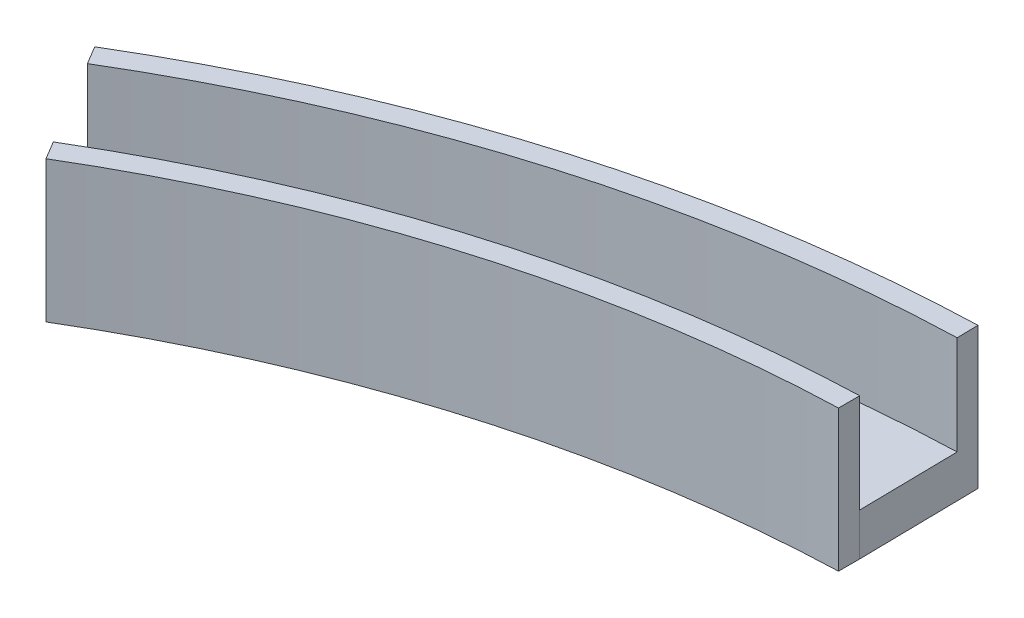
SolidWorks part; units mm, degrees
material "AISI 316 Stainless Steel Sheet (SS)"
ref_plane "Front Plane" through (0, 0, 0) normal (0, 0, 1) x (1, 0, 0)
ref_plane "Top Plane" through (0, 0, 0) normal (0, 1, 0) x (1, 0, 0)
ref_plane "Right Plane" through (0, 0, 0) normal (1, 0, 0) x (0, 0, -1)
sketch "Sketch2" plane through (0, 0, 0) normal (0, 1, 0) x (1, 0, 0)
  line L0 (-51.5041, 86.0722) -> (-47.1395, 78.7783)
  line L2 (-3.1971, 100.254) -> (-3.0643, 91.7538)
  line L3 (-47.1395, 78.7783) -> (-46.3693, 77.4912)
  line L4 (-3.0643, 91.7538) -> (-3.0643, 90.253)
  arc A0 (-51.5041, 86.0722) -> (-3.1971, 100.254) centre (0, 0) cw
  arc A1 (-47.1395, 78.7783) -> (-3.0643, 91.7538) centre (0, 0) cw construction
  arc A2 (-46.3693, 77.4912) -> (-3.0643, 90.253) centre (0, 0) cw
  dimension "D2" = 91.805
  dimension "D3" = 8.5002
  dimension "D1" = 8.5
  dimension "D4" = 30
  dimension "D5" = 1.5
  dimension "D6" = 1.5009
extrude "Boss-Extrude1" add sketch "Sketch2" along normal blind 10
sketch "Sketch4" plane through (0, 10, 0) normal (0, 1, 0) x (1, 0, 0)
  line L0 (-51.5041, 86.0722) -> (-46.3693, 77.4912) construction
  line L1 (-3.0643, 91.7538) -> (-3.1971, 100.254) construction
  line L2 (-50.7338, 84.785) -> (-47.1395, 78.7783)
  line L3 (-3.1737, 98.754) -> (-3.0643, 91.7538)
  arc A0 (-47.1395, 78.7783) -> (-3.0643, 91.7538) centre (0, 0) cw
  arc A1 (-3.0643, 90.253) -> (-46.3693, 77.4912) centre (0, 0) ccw construction
  arc A2 (-50.7338, 84.785) -> (-3.1737, 98.754) centre (0, 0) cw
  dimension "D1" = 1.5
  dimension "D2" = 7
extrude "Cut-Extrude1" cut sketch "Sketch4" against normal blind 7
